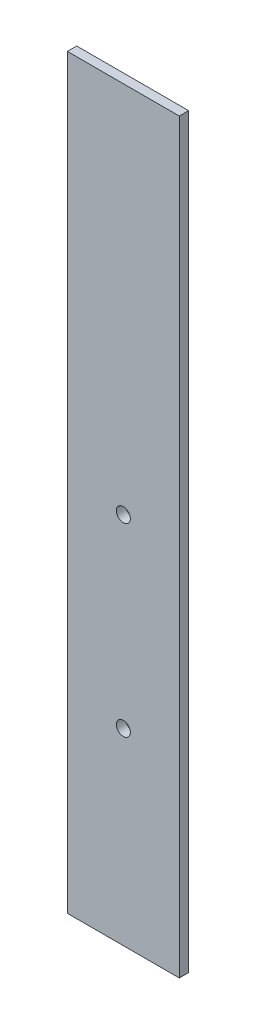
SolidWorks part; units mm, degrees
ref_plane "Front Plane" through (0, 0, 0) normal (0, 0, 1) x (1, 0, 0)
ref_plane "Top Plane" through (0, 0, 0) normal (0, 1, 0) x (1, 0, 0)
ref_plane "Right Plane" through (0, 0, 0) normal (1, 0, 0) x (0, 0, -1)
sketch "Sketch1" plane through (0, 0, 0) normal (0, 0, 1) x (1, 0, 0)
  line L1 (0, 0) -> (38.1, 0)
  line L2 (0, 0) -> (0, -254)
  line L3 (0, -254) -> (38.1, -254)
  line L4 (38.1, 0) -> (38.1, -254)
  circle A0 centre (19.05, -127) radius 2.3813
  circle A1 centre (19.05, -189.971) radius 2.3813
extrude "Boss-Extrude1" add sketch "Sketch1" along normal blind 3.175
